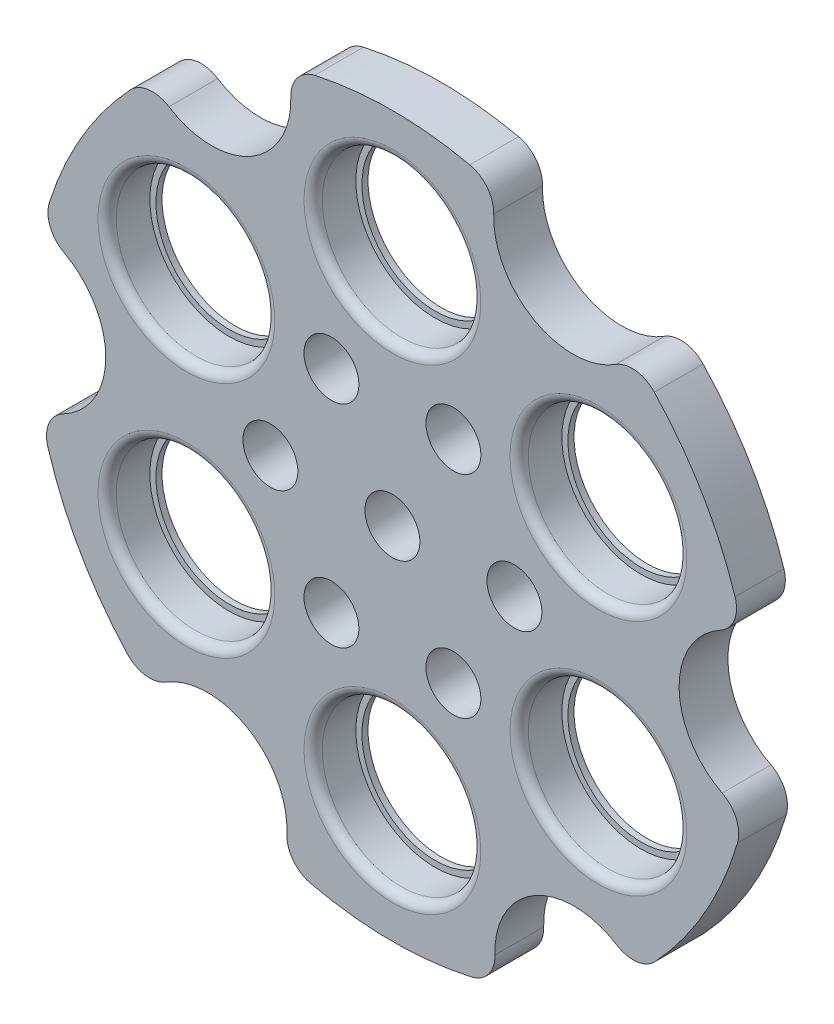
SolidWorks part; units mm, degrees
ref_plane "Front Plane" through (0, 0, 0) normal (0, 0, 1) x (1, 0, 0)
ref_plane "Top Plane" through (0, 0, 0) normal (0, 1, 0) x (1, 0, 0)
ref_plane "Right Plane" through (0, 0, 0) normal (1, 0, 0) x (0, 0, -1)
sketch "Sketch1" plane through (0, 0, 0) normal (0, 0, 1) x (1, 0, 0)
  line L0 (0, 64.3662) -> (0, -64.9261) construction
  line L1 (0, 0) -> (65.4373, 37.7803) construction
  line L2 (0, 0) -> (75.2504, -43.4458) construction
  line L3 (0, 0) -> (-59.2673, 34.218) construction
  line L4 (0, 0) -> (-59.8259, -34.5405) construction
  line L12 (0, -64.9261) -> (0, -63.7788) construction
  arc A0 (-39.5746, 43.7591) -> (-57.5043, 13.2007) centre (0, 0) ccw
  arc A7 (-17.3604, 56.3881) -> (-39.5746, 43.7591) centre (-29.6536, 52.16) cw
  arc A8 (-57.5043, 13.2007) -> (-57.6926, -12.3517) centre (-59.9984, 0.4422) cw
  arc A9 (-40.1066, -43.2719) -> (-18.0485, -56.1716) centre (-30.2891, -51.7935) cw
  arc A10 (17.5127, -56.341) -> (39.6926, -43.652) centre (29.7944, -52.0797) cw
  arc A11 (57.4535, 13.42) -> (57.7396, -12.1301) centre (60, 0.6719) ccw
  arc A12 (17.3045, 56.4053) -> (39.5311, 43.7983) centre (29.6019, 52.1894) ccw
  arc A13 (-57.6926, -12.3517) -> (-40.1066, -43.2719) centre (0, 0) ccw
  arc A14 (-18.0485, -56.1716) -> (17.5127, -56.341) centre (0, 0) ccw
  arc A15 (39.6926, -43.652) -> (57.7396, -12.1301) centre (0, 0) ccw
  arc A16 (57.4535, 13.42) -> (39.5311, 43.7983) centre (0, 0) ccw
  arc A17 (17.3045, 56.4053) -> (-17.3604, 56.3881) centre (0, 0) ccw
  point P24 (0, 0)
  point P38 (-0.2277, 0.6984)
  dimension "D4" = 13
  dimension "D6" = 118
  dimension "D7" = 13
  dimension "D5" = 13
  dimension "D8" = 13
  dimension "D9" = 13
  dimension "D10" = 13
  dimension "D11" = 60
  dimension "D1" = 60
  dimension "D2" = 60
  dimension "D3" = 60
  dimension "D12" = 60
  dimension "D13" = 60
  dimension "D14" = 60
  dimension "D15" = 60
  dimension "D16" = 60
extrude "Boss-Extrude1" add sketch "Sketch1" along normal blind 8
sketch "Sketch5" plane through (0, 0, 8) normal (0, 0, 1) x (1, 0, 0)
  line L0 (0, -50.127) -> (0, 54.619) construction
  circle A0 centre (0, 39) radius 13
  circle A17 centre (33.775, 19.5) radius 13
  circle A18 centre (33.775, -19.5) radius 13
  circle A19 centre (0, -39) radius 13
  circle A20 centre (-33.775, -19.5) radius 13
  circle A21 centre (-33.775, 19.5) radius 13
  point P18 (-4.3301, 2.5)
  point P19 (-1.7321, 1)
  point P20 (2.5981, -1.5)
  point P21 (0, 0)
  dimension "D1" = 26
  dimension "D3" = 6
  dimension "D2" = 39
extrude "Cut-Extrude2" cut sketch "Sketch5" against normal blind 7
sketch "Sketch6" plane through (0, 0, 8) normal (0, 0, 1) x (1, 0, 0)
  line L0 (0, 52.5772) -> (0, -53.5981) construction
  circle A1 centre (0, 39) radius 12
  circle A11 centre (33.775, 19.5) radius 12
  circle A12 centre (33.775, -19.5) radius 12
  circle A13 centre (0, -39) radius 12
  circle A14 centre (-33.775, -19.5) radius 12
  circle A15 centre (-33.775, 19.5) radius 12
  point P17 (0, 0)
  point P18 (-8.6603, 5)
  point P21 (2.5981, -1.5)
  point P22 (0, 0)
  dimension "D1" = 24
  dimension "D2" = 6
extrude "Cut-Extrude4" cut sketch "Sketch6" against normal through all
fillet "Fillet1" radius 5 12 edges at (-57.5043, 13.2007, 4) (-57.6926, -12.3517, 4) (-40.1066, -43.2719, 4) (-18.0485, -56.1716, 4) (17.5127, -56.341, 4) (39.6926, -43.652, 4) (57.7396, -12.1301, 4) (57.4535, 13.42, 4) (39.5311, 43.7983, 4) (17.3045, 56.4053, 4) (-39.5746, 43.7591, 4) (-17.3604, 56.3881, 4)
fillet "Fillet2" radius 1.5 6 edges at (13, 39, 8) (13, -39, 8) (46.775, -19.5, 8) (-20.775, -19.5, 8) (-20.775, 19.5, 8) (46.775, 19.5, 8)
sketch "Sketch4" plane through (0, 0, 0) normal (0, 0, -1) x (-1, 0, 0)
  circle A0 centre (0, 0) radius 4.5
  dimension "D1" = 9
extrude "Cut-Extrude1" cut sketch "Sketch4" against normal through all
sketch "Sketch7" plane through (0, 0, 0) normal (0, 0, -1) x (-1, 0, 0)
  line L0 (0, 0) -> (75.8692, 0) construction
  line L1 (75.8692, 0) -> (-68.497, 0) construction
  line L2 (0, 0) -> (0, 69.5902) construction
  line L3 (0, 0) -> (0, -62.2392) construction
  line L4 (0, 0) -> (73.8818, 42.6557) construction
  line L5 (73.8818, 42.6557) -> (-71.9539, -41.5426) construction
  line L6 (0, 0) -> (78.2175, -45.1589) construction
  line L7 (78.2175, -45.1589) -> (-75.2057, 43.4201) construction
  line L8 (0, 0) -> (-39.9206, 69.1446) construction
  circle A0 centre (-10, 17.3205) radius 4.5
  circle A1 centre (10, 17.3205) radius 4.5
  circle A2 centre (20, 0) radius 4.5
  circle A3 centre (10, -17.3205) radius 4.5
  circle A4 centre (-10, -17.3205) radius 4.5
  circle A5 centre (-20, 0) radius 4.5
  point P26 (0, 0)
  dimension "D4" = 9
  dimension "D1" = 30
  dimension "D2" = 30
  dimension "D3" = 30
  dimension "D5" = 20
  dimension "D6" = 6
extrude "Cut-Extrude5" cut sketch "Sketch7" against normal through all
